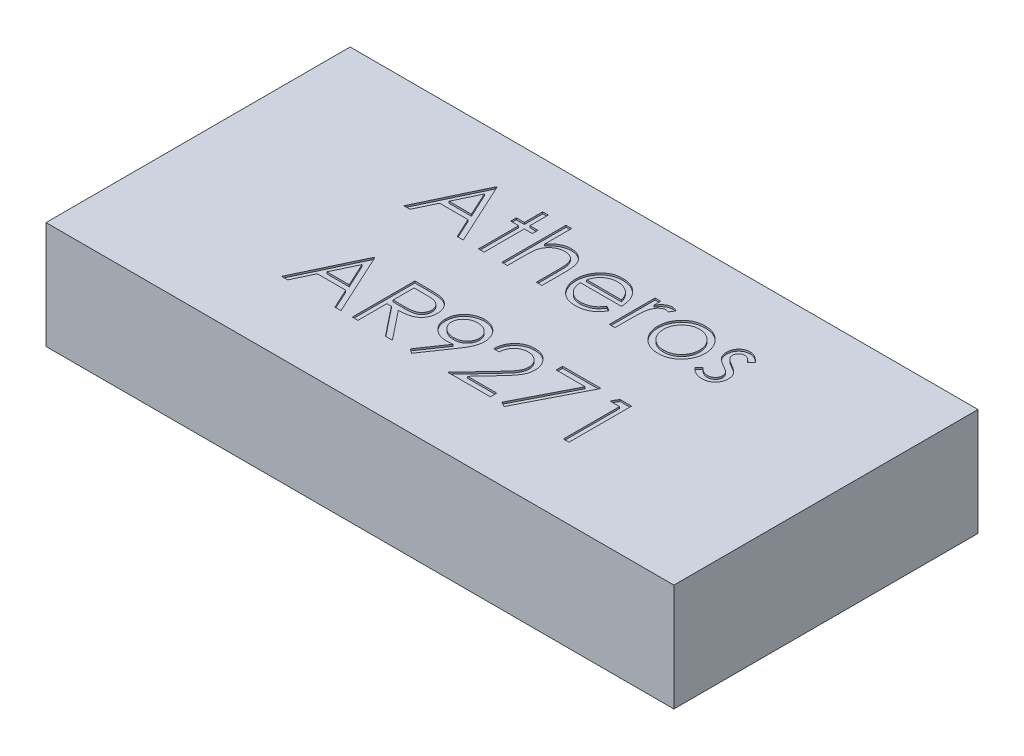
SolidWorks part; units mm, degrees
ref_plane "Front Plane" through (0, 0, 0) normal (0, 0, 1) x (1, 0, 0)
ref_plane "Top Plane" through (0, 0, 0) normal (0, 1, 0) x (1, 0, 0)
ref_plane "Right Plane" through (0, 0, 0) normal (1, 0, 0) x (0, 0, -1)
sketch "Sketch1" plane through (0, 0, 0) normal (0, 1, 0) x (1, 0, 0)
  line L1 (0, 0) -> (35.1, 0)
  line L2 (0, 0) -> (0, 17)
  line L3 (0, 17) -> (35.1, 17)
  line L4 (35.1, 0) -> (35.1, 17)
  dimension "D1" = 35.1
  dimension "D2" = 17
extrude "Boss-Extrude1" add sketch "Sketch1" along normal blind 6
sketch "Sketch2" plane through (0, 6, 0) normal (0, 1, 0) x (1, 0, 0)
  text T0 "Atheros\r\nAR9271"
extrude "Cut-Extrude1" cut sketch "Sketch2" against normal blind 0.1
